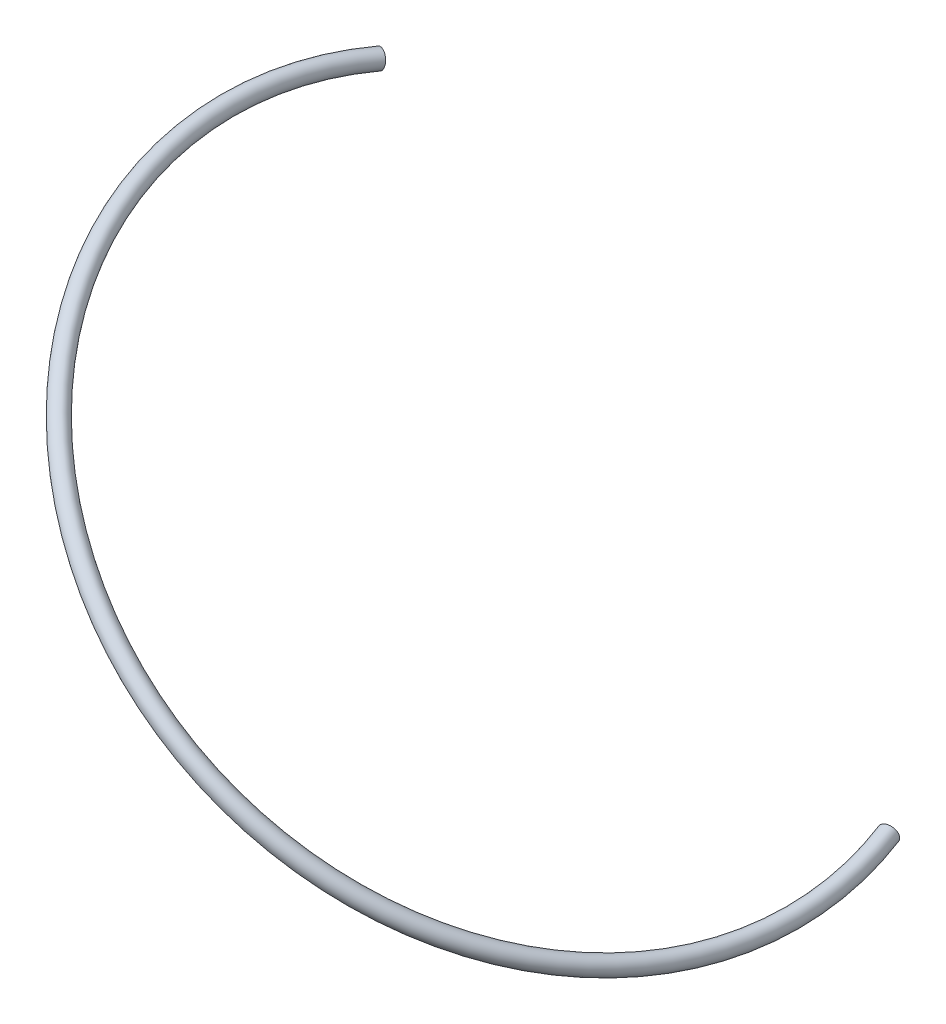
SolidWorks part; units mm, degrees
material "PVC 0.007 Plasticized"
ref_plane "Front Plane" through (0, 0, 0) normal (0, 0, 1) x (1, 0, 0)
ref_plane "Top Plane" through (0, 0, 0) normal (0, 1, 0) x (1, 0, 0)
ref_plane "Right Plane" through (0, 0, 0) normal (1, 0, 0) x (0, 0, -1)
sketch3d "3DSketch1"
  circle A0 centre (121.25, 25.85, 22.25) radius 3.5 construction
  circle A1 centre (121.25, 25.85, 22.25) radius 3.5 construction
  circle A2 centre (240.75, -63.2, 27) radius 3.5 construction
  circle A3 centre (240.75, -63.2, 27) radius 3.5 construction
  point P2 (121.25, 25.85, 25.75)
  point P4 (121.25, 25.85, 25.75)
  point P7 (240.75, -63.2, 30.5)
  point P9 (240.75, -63.2, 30.5)
  point P10 (121.25, 25.85, 22.25)
  point P11 (240.75, -63.2, 27)
ref_plane "Plane1" through (55.6765, 74.7146, 0) normal (0.5975, 0.8018, 0) x (0.8018, -0.5975, 0)
sketch "Sketch2" plane through (55.6765, 74.7146, 0) normal (0.5975, 0.8018, 0) x (0.8018, -0.5975, 0)
  arc A0 (81.778, -22.25) -> (230.8087, -27) centre (155.4273, -51.7979) ccw
  dimension "D1" = 304.8
sweep "Sweep1" add path "Sketch2" circular profile diameter 4 parameters "D3"=4
